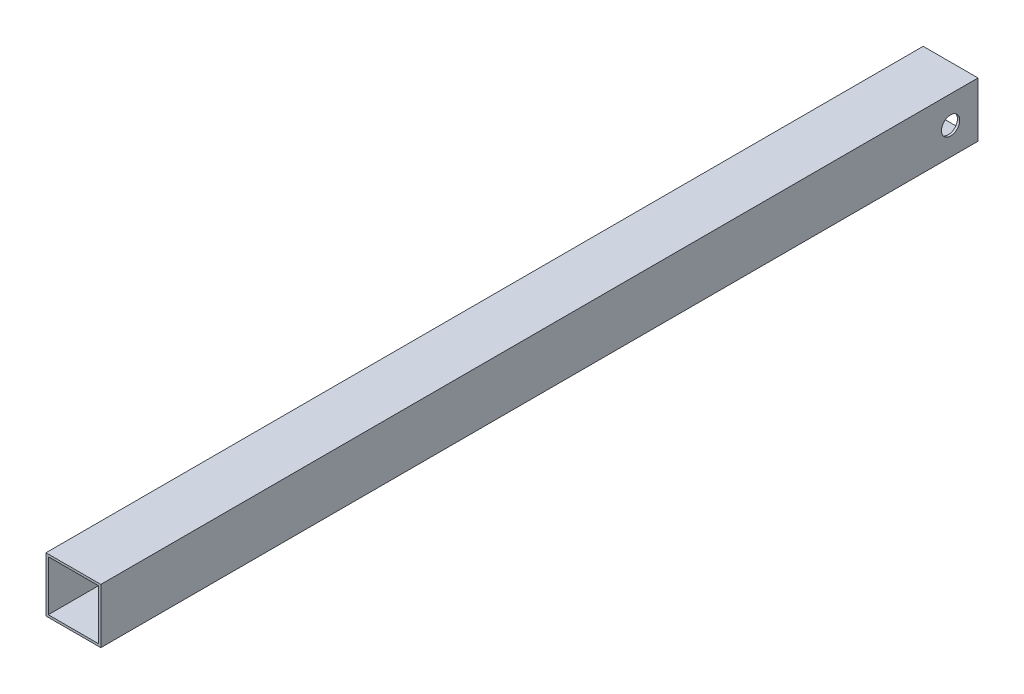
SolidWorks part; units mm, degrees
material "Plain Carbon Steel"
ref_plane "Front Plane" through (0, 0, 0) normal (0, 0, 1) x (1, 0, 0)
ref_plane "Top Plane" through (0, 0, 0) normal (0, 1, 0) x (1, 0, 0)
ref_plane "Right Plane" through (0, 0, 0) normal (1, 0, 0) x (0, 0, -1)
sketch "Sketch2" plane through (0, 0, 0) normal (0, 0, 1) x (1, 0, 0)
  line L0 (0, 19.05) -> (1.5875, 19.05) construction
  line L1 (0, 0) -> (38.1, 0)
  line L2 (0, 0) -> (0, 38.1)
  line L3 (0, 38.1) -> (38.1, 38.1)
  line L4 (38.1, 0) -> (38.1, 38.1)
  line L5 (1.5875, 1.5875) -> (36.5125, 1.5875)
  line L6 (1.5875, 1.5875) -> (1.5875, 36.5125)
  line L7 (1.5875, 36.5125) -> (36.5125, 36.5125)
  line L8 (36.5125, 1.5875) -> (36.5125, 36.5125)
  line L9 (19.05, 36.5125) -> (19.05, 38.1) construction
  line L10 (36.5125, 19.05) -> (38.1, 19.05) construction
  line L11 (19.05, 0) -> (19.05, 1.5875) construction
  dimension "D1" = 38.1
  dimension "D2" = 1.5875
  dimension "D3" = 38.1
extrude "Boss-Extrude1" add sketch "Sketch2" along normal blind 609.6
hole_wizard "1/2 (0.5) Diameter Hole1" positions "Sketch4" profile "Sketch3" hole size "1/2" standard "ANSI Inch" end condition through all
sketch "Sketch4" plane through (0, 0, 0) normal (-1, 0, 0) x (0, 0, 1)
  line L0 (0, 19.05) -> (19.05, 19.05) construction
  line L1 (0, 38.1) -> (0, 0) construction
  point P0 (19.05, 19.05)
  dimension "D1" = 19.05
sketch "Sketch3" plane through (0, 19.05, 19.05) normal (0, 1, 0) x (0, 0, 1)
  line L0 (0, 0) -> (0, 38.1)
  line L1 (0, 38.1) -> (6.35, 38.1)
  line L2 (6.35, 38.1) -> (6.35, 0)
  line L5 (6.35, 0) -> (0, 0)
  line L11 (0, -6.35) -> (0, 107.95) construction
  dimension "Thru Hole Dia." = 12.7
  dimension "Thru Hole Depth" = 38.1
